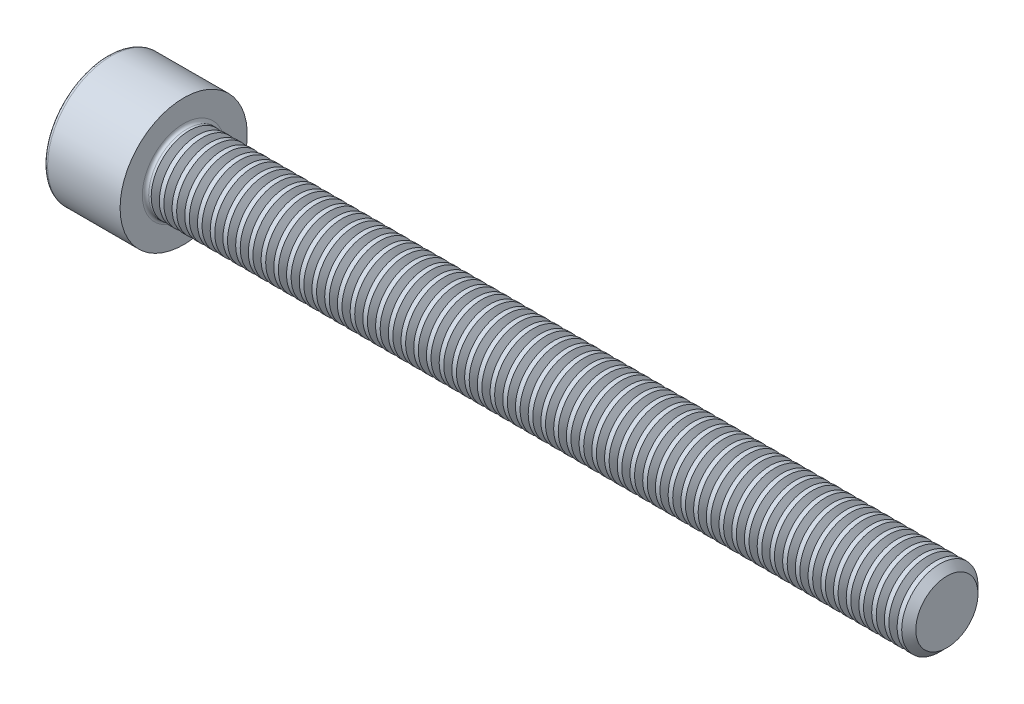
SolidWorks part; units mm, degrees
ref_plane "Front Plane" through (0, 0, 0) normal (0, 0, 1) x (1, 0, 0)
ref_plane "Top Plane" through (0, 0, 0) normal (0, 1, 0) x (1, 0, 0)
ref_plane "Right Plane" through (0, 0, 0) normal (1, 0, 0) x (0, 0, -1)
sketch "BodySke" plane through (0, 0, 0) normal (0, 0, 1) x (1, 0, 0)
  line L0 (0, 0) -> (5.8492, 0) construction
  line L1 (0, 0) -> (0, 5)
  line L2 (0, 5) -> (6, 5)
  line L3 (6, 5) -> (6, 3)
  line L4 (6, 3) -> (65.4455, 3)
  line L5 (65.4455, 3) -> (66, 2.4455)
  line L6 (66, 2.4455) -> (66, 0)
  line L7 (66, 0) -> (0, 0)
  line L8 (6, 0) -> (6, 0.601) construction
  line L9 (7, 1.5877) -> (7, 0.9267) construction
  dimension "Thread_length" = 60
  dimension "Diameter" = 6
  dimension "Thread_minor" = 4.891
  dimension "Body_chamfer_angle" = 45
  dimension "Length" = 60
  dimension "Head_diameter" = 10
  dimension "Head_length" = 6
  dimension "Advance" = 1
revolve "BaseBody" add sketch "BodySke" angle 360 about L0
cosmetic thread "ThreadCosmetic" [suppressed] parameters "Thread_length"=60, "Thread_minor"=4.891
fillet "Fillet1" radius 0.25 1 edges at (6, 0, 3)
fillet "Fillet2" radius 0.3 1 edges at (0, 0, 5)
sketch "HexSke" plane through (0, 0, 0) normal (1, 0, 0) x (0, 0, -1)
  line L1 (0, 2.8868) -> (-2.5, 1.4434)
  line L2 (-2.5, 1.4434) -> (-2.5, -1.4434)
  line L3 (-2.5, -1.4434) -> (0, -2.8868)
  line L4 (0, -2.8868) -> (2.5, -1.4434)
  line L5 (2.5, -1.4434) -> (2.5, 1.4434)
  line L6 (2.5, 1.4434) -> (0, 2.8868)
  circle A0 centre (0, 0) radius 2.5 construction
  dimension "Hex_size" = 5
extrude "Hex" cut sketch "HexSke" along normal blind 3
sketch "Hex-PreBroachSke" plane through (0, 0, 0) normal (0, 0, 1) x (1, 0, 0)
  line L0 (0, 0) -> (4.7325, 0) construction
  line L1 (0, 4.7) -> (0, -4.7) construction
  line L2 (0, 0) -> (0, 2.5)
  line L3 (0, 2.5) -> (3, 2.5)
  line L4 (3, 2.5) -> (4.4434, 0)
  line L5 (4.4434, 0) -> (0, 0)
  dimension "Hex_depth" = 3
  dimension "D1" = 5
  dimension "Angle" = 60
revolve "Hex-PreBroach" cut sketch "Hex-PreBroachSke" angle 360 about L0
sketch "ThdSchSke" plane through (0, 0, 0) normal (0, 0, 1) x (1, 0, 0)
  line L0 (0, 0) -> (4.4125, 0) construction
  line L1 (0, 4.7) -> (0, -4.7) construction
  line L2 (64.4455, 3.6403) -> (64.4455, 3)
  line L3 (64.4455, 3.6403) -> (65.0858, 3.6403)
  line L4 (65.0858, 3.6403) -> (65.0858, 3)
  line L5 (65.0858, 3) -> (64.7656, 2.4455)
  line L6 (64.7656, 2.4455) -> (64.4455, 3)
  dimension "D1" = 1
revolve "ThreadSchematic" cut sketch "ThdSchSke" angle 360 about L0
pattern_linear "ThdSchPat" count 59 spacing 1 along (-1, 0, 0) of "ThreadSchematic"
equation "\"Thread_length@ThreadCosmetic\" = \"Thread_length@BodySke\""
equation "\"Thread_minor@ThreadCosmetic\" = \"Thread_minor@BodySke\""
equation "\"Hex_depth@Hex-PreBroachSke\" = \"Hex_length@Hex\""
equation "\"D1@Hex-PreBroachSke\" = \"Hex_size@HexSke\""
equation "\"D1@ThdSchSke\" = \"Advance@BodySke\""
equation "\"Advance@ThdSchPat\" = \"Advance@BodySke\""
equation "\"Tooth_Num@ThdSchPat\" =  int( \"Thread_length@BodySke\" / \"Advance@BodySke\" )  - 1"
